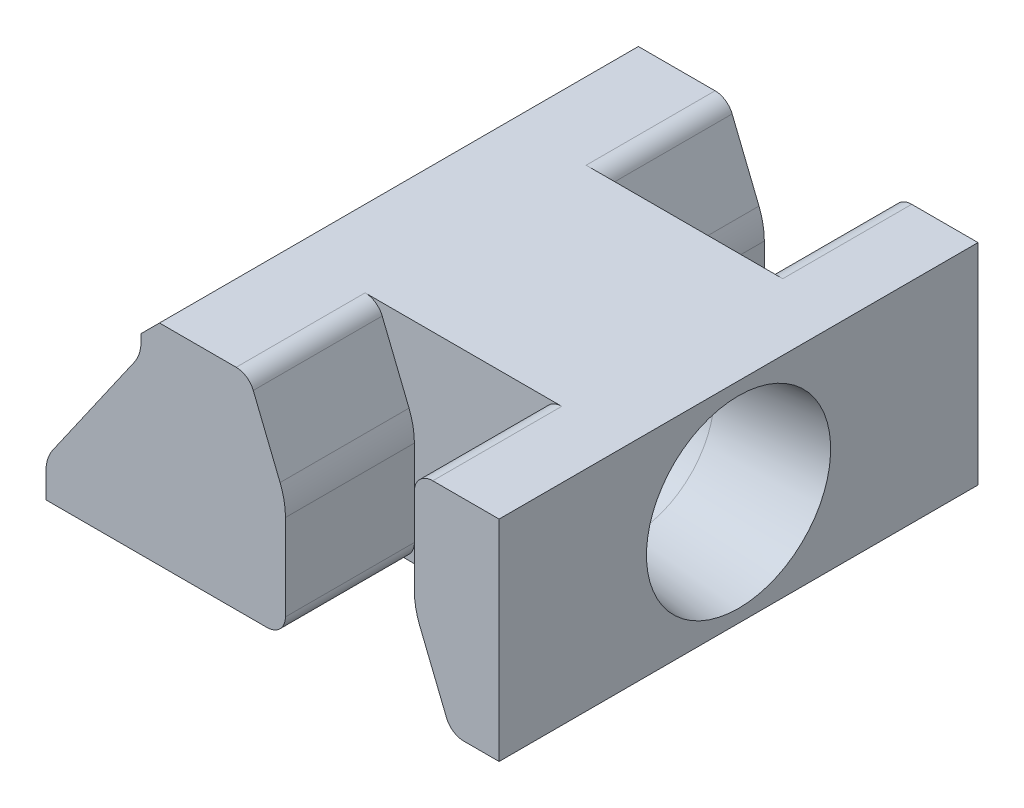
SolidWorks part; units mm, degrees
ref_plane "Front Plane" through (0, 0, 0) normal (0, 0, 1) x (1, 0, 0)
ref_plane "Top Plane" through (0, 0, 0) normal (0, 1, 0) x (1, 0, 0)
ref_plane "Right Plane" through (0, 0, 0) normal (1, 0, 0) x (0, 0, -1)
sketch "Sketch1" plane through (0, 0, 0) normal (0, 0, 1) x (1, 0, 0)
  line L0 (-2.7823, -2.5959) -> (-0.2019, 1.1041)
  line L1 (-0.2019, 2.1041) -> (9.5177, 2.1041)
  line L2 (-2.7823, -2.5959) -> (-2.7823, -3.5959)
  line L3 (-2.7823, -3.5959) -> (9.5177, -3.5959)
  line L4 (9.5177, 2.1041) -> (9.5177, -3.5959)
  line L5 (-0.2019, 1.1041) -> (-0.2019, 2.1041)
  dimension "D1" = 12.3
  dimension "D2" = 5.7
  dimension "D3" = 1
  dimension "D4" = 1
  dimension "D5" = 2.5803
extrude "Boss-Extrude1" add sketch "Sketch1" along normal blind 13
sketch "Sketch2" plane through (0, 2.1041, 0) normal (0, 1, 0) x (1, 0, 0)
  line L1 (3.7177, 0) -> (7.2177, 0)
  line L2 (3.7177, 0) -> (3.7177, -3.5)
  line L3 (3.7177, -3.5) -> (7.2177, -3.5)
  line L4 (7.2177, 0) -> (7.2177, -3.5)
  line L5 (9.5177, -6.5) -> (-2.7823, -6.5) construction
  line L6 (9.5177, -13) -> (9.5177, 0) construction
  line L8 (9.5177, 0) -> (-0.2019, 0) construction
  line L9 (7.2177, -13) -> (7.2177, -9.5)
  line L10 (3.7177, -9.5) -> (7.2177, -9.5)
  line L11 (3.7177, -13) -> (3.7177, -9.5)
  line L12 (3.7177, -13) -> (7.2177, -13)
  line L14 (-2.7823, -13) -> (-2.7823, 0) construction
  dimension "D1" = 2.3
  dimension "D2" = 3.5
  dimension "D3" = 3
extrude "Cut-Extrude1" cut sketch "Sketch2" against normal up to next
chamfer "Chamfer3" distance 1 angle 68 4 edges at (3.7177, 2.1041, 11.25) (7.2177, -3.5959, 11.25) (7.2177, -3.5959, 1.75) (3.7177, 2.1041, 1.75)
sketch "Sketch4" plane through (9.5177, 0, 0) normal (1, 0, 0) x (0, 0, -1)
  line L0 (-13, 2.1041) -> (0, 2.1041) construction
  line L2 (-6.5, 2.1041) -> (-6.5, -3.5959) construction
  line L7 (-13, -3.5959) -> (0, -3.5959) construction
  circle A0 centre (-6.5, -0.7459) radius 2.2
  dimension "D1" = 4.4
extrude "Cut-Extrude3" cut sketch "Sketch4" against normal blind 9
fillet "Fillet1" radius 1 2 edges at (-2.7823, -2.5959, 6.5) (-0.2019, 1.1041, 6.5)
chamfer "Chamfer4" distance 0.5 angle 45 1 edges at (-0.2019, 2.1041, 6.5)
fillet "Fillet2" radius 2 4 edges at (3.7177, -0.371, 1.75) (7.2177, -1.1208, 1.75) (3.7177, -0.371, 11.25) (7.2177, -1.1208, 11.25)
fillet "Fillet3" radius 0.5 8 edges at (7.2177, 2.1041, 1.75) (7.2177, 2.1041, 11.25) (2.7177, 2.1041, 11.25) (3.7177, -3.5959, 11.25) (2.7177, 2.1041, 1.75) (3.7177, -3.5959, 1.75) (8.2177, -3.5959, 1.75) (8.2177, -3.5959, 11.25)
chamfer "Chamfer5" distance 0.3 angle 84 1 edges at (9.5177, 1.4541, 6.5)
